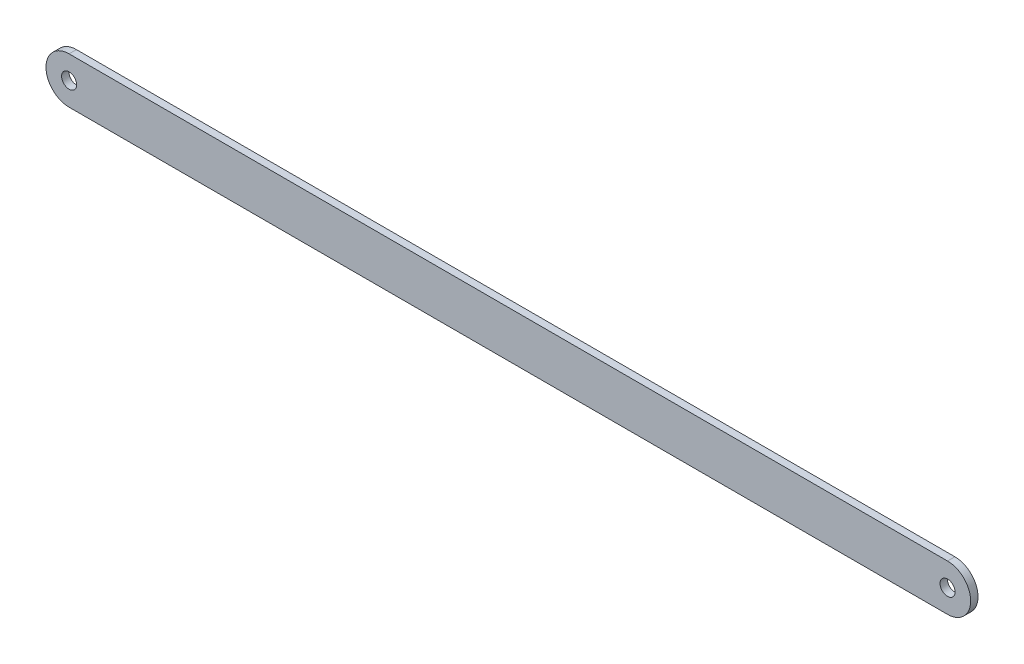
SolidWorks part; units mm, degrees
material "AISI 1020 Steel, Cold Rolled"
ref_plane "Front Plane" through (0, 0, 0) normal (0, 0, 1) x (1, 0, 0)
ref_plane "Top Plane" through (0, 0, 0) normal (0, 1, 0) x (1, 0, 0)
ref_plane "Right Plane" through (0, 0, 0) normal (1, 0, 0) x (0, 0, -1)
sketch "Sketch1" plane through (0, 0, 0) normal (0, 0, 1) x (1, 0, 0)
  line L0 (0, 0) -> (380, 0) construction
  line L1 (0, 10) -> (380, 10)
  line L2 (0, -10) -> (380, -10)
  arc A0 (0, 10) -> (0, -10) centre (0, 0) ccw
  arc A1 (380, -10) -> (380, 10) centre (380, 0) ccw
  circle A2 centre (0, 0) radius 3.25
  circle A3 centre (380, 0) radius 3.25
  point P3 (190, 0)
  dimension "D2" = 6.5
  dimension "D3" = 10
  dimension "D1" = 380
extrude "Boss-Extrude1" add sketch "Sketch1" along normal blind 3.175
